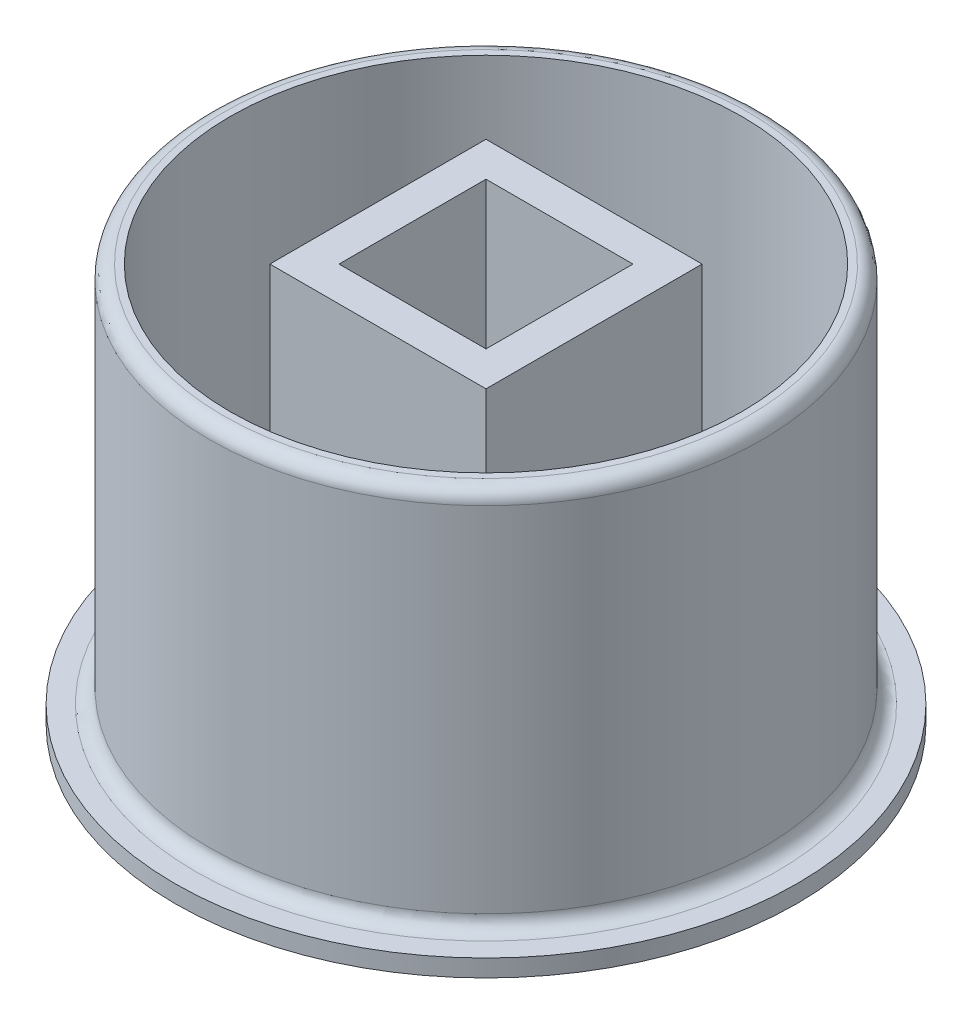
SolidWorks part; units mm, degrees
ref_plane "Front Plane" through (0, 0, 0) normal (0, 0, 1) x (1, 0, 0)
ref_plane "Top Plane" through (0, 0, 0) normal (0, 1, 0) x (1, 0, 0)
ref_plane "Right Plane" through (0, 0, 0) normal (1, 0, 0) x (0, 0, -1)
sketch "Sketch1" plane through (0, 0, 0) normal (0, 1, 0) x (1, 0, 0)
  circle A0 centre (0, 0) radius 57.15
  dimension "D1" = 114.3
extrude "Boss-Extrude1" add sketch "Sketch1" along normal blind 3.175
sketch "Sketch2" plane through (0, 3.175, 0) normal (0, 1, 0) x (1, 0, 0)
  circle A0 centre (0, 0) radius 50.8
  dimension "D1" = 101.6
extrude "Boss-Extrude2" add sketch "Sketch2" along normal blind 70
sketch "Sketch3" plane through (0, 73.175, 0) normal (0, 1, 0) x (1, 0, 0)
  line L1 (-13.5, 13.5) -> (13.5, 13.5)
  line L2 (-13.5, 13.5) -> (-13.5, -13.5)
  line L3 (-13.5, -13.5) -> (13.5, -13.5)
  line L4 (13.5, 13.5) -> (13.5, -13.5)
  line L5 (-13.5, 13.5) -> (13.5, -13.5) construction
  line L6 (-13.5, -13.5) -> (13.5, 13.5) construction
  line L7 (-19.85, 19.85) -> (19.85, 19.85)
  line L8 (-19.85, 19.85) -> (-19.85, -19.85)
  line L9 (-19.85, -19.85) -> (19.85, -19.85)
  line L10 (19.85, 19.85) -> (19.85, -19.85)
  line L11 (-19.85, 19.85) -> (19.85, -19.85) construction
  line L12 (-19.85, -19.85) -> (19.85, 19.85) construction
  point P0 (0, 0)
  point P7 (0, 0)
  dimension "D1" = 27
  dimension "D2" = 27
  dimension "D3" = 6.35
  dimension "D4" = 6.35
shell "Shell3" thickness 3.81
extrude "Boss-Extrude3" add sketch "Sketch3" against normal up to next
fillet "Fillet2" radius 2.54 2 edges at (0, 3.175, 50.8) (0, 73.175, 50.8)
sketch "Sketch4" plane through (0, 3.81, 0) normal (0, 1, 0) x (1, 0, 0)
  line L1 (-13.5, 13.5) -> (13.5, 13.5)
  line L2 (-13.5, 13.5) -> (-13.5, -13.5)
  line L3 (-13.5, -13.5) -> (13.5, -13.5)
  line L4 (13.5, 13.5) -> (13.5, -13.5)
  line L5 (-13.5, 13.5) -> (13.5, -13.5) construction
  line L6 (-13.5, -13.5) -> (13.5, 13.5) construction
  point P0 (0, 0)
extrude "Boss-Extrude5" add sketch "Sketch4" along normal blind 40
